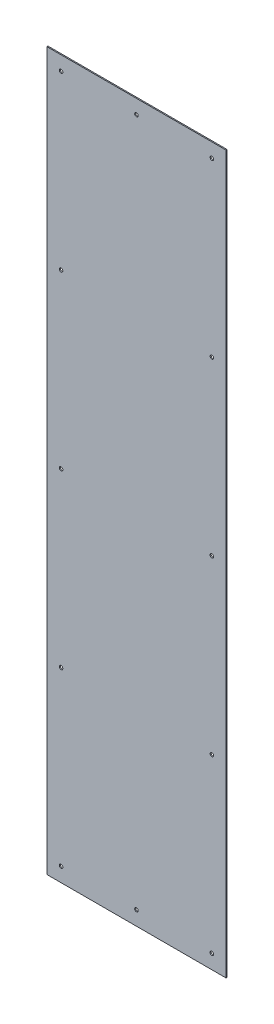
SolidWorks part; units mm, degrees
ref_plane "Alzado" through (0, 0, 0) normal (0, 0, 1) x (1, 0, 0)
ref_plane "Planta" through (0, 0, 0) normal (0, 1, 0) x (1, 0, 0)
ref_plane "Vista lateral" through (0, 0, 0) normal (1, 0, 0) x (0, 0, -1)
sketch "Croquis1" plane through (0, 0, 0) normal (0, 0, 1) x (1, 0, 0)
  line L1 (-160, 640) -> (160, 640)
  line L2 (-160, 640) -> (-160, -640)
  line L3 (-160, -640) -> (160, -640)
  line L4 (160, 640) -> (160, -640)
  line L5 (-160, 640) -> (160, -640) construction
  line L6 (-160, -640) -> (160, 640) construction
  point P0 (0, 0)
  dimension "D1" = 320
  dimension "D2" = 1280
extrude "Saliente-Extruir1" add sketch "Croquis1" along normal blind 1.9
sketch "Croquis2" plane through (0, 0, 1.9) normal (0, 0, 1) x (1, 0, 0)
  line L0 (160, 640) -> (-160, 640) construction
  line L1 (-134.6, -614.6) -> (134.6, -614.6) construction
  line L2 (-134.6, -614.6) -> (-134.6, 614.6) construction
  line L3 (-134.6, 614.6) -> (134.6, 614.6) construction
  line L4 (134.6, -614.6) -> (134.6, 614.6) construction
  line L5 (-134.6, -614.6) -> (134.6, 614.6) construction
  line L6 (-134.6, 614.6) -> (134.6, -614.6) construction
  line L7 (-160, 640) -> (-160, -640) construction
  line L8 (0, 0) -> (0, 323.201) construction
  line L9 (0, 0) -> (-134.6, 0) construction
  line L10 (-134.6, 0) -> (-134.6, 614.6) construction
  line L11 (-134.6, 614.6) -> (-134.6, 307.3) construction
  line L12 (-134.6, 307.3) -> (134.6, 307.3) construction
  line L13 (-134.6, 0) -> (-134.6, -614.6) construction
  line L14 (-134.6, -614.6) -> (-134.6, -307.3) construction
  line L15 (-134.6, -307.3) -> (134.6, -307.3) construction
  circle A0 centre (-134.6, 614.6) radius 3.175
  circle A1 centre (134.6, 614.6) radius 3.175
  circle A2 centre (134.6, -614.6) radius 3.175
  circle A3 centre (-134.6, -614.6) radius 3.175
  circle A4 centre (0, 614.6) radius 3.175
  circle A5 centre (0, -614.6) radius 3.175
  circle A6 centre (-134.6, 0) radius 3.175
  circle A7 centre (134.6, 0) radius 3.175
  circle A8 centre (-134.6, -307.3) radius 3.175
  circle A9 centre (134.6, -307.3) radius 3.175
  circle A10 centre (-134.6, 307.3) radius 3.175
  circle A11 centre (134.6, 307.3) radius 3.175
  point P0 (0, 0)
  dimension "D3" = 6.35
  dimension "D4" = 6.35
  dimension "D5" = 6.35
  dimension "D6" = 6.35
  dimension "D7" = 6.35
  dimension "D8" = 6.35
  dimension "D1" = 25.4
  dimension "D2" = 25.4
extrude "Cortar-Extruir1" cut sketch "Croquis2" against normal blind 10
